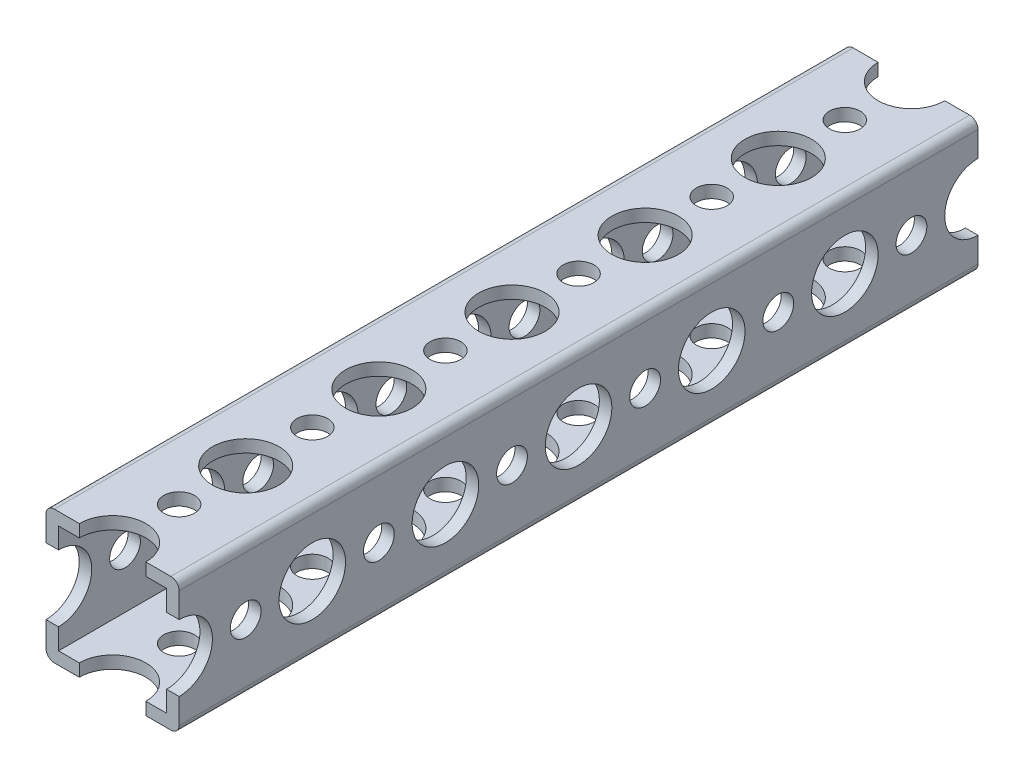
SolidWorks part; units mm, degrees
ref_plane "Front Plane" through (0, 0, 0) normal (0, 0, 1) x (1, 0, 0)
ref_plane "Top Plane" through (0, 0, 0) normal (0, 1, 0) x (1, 0, 0)
ref_plane "Right Plane" through (0, 0, 0) normal (1, 0, 0) x (0, 0, -1)
sketch "Sketch1" plane through (0, 0, 0) normal (0, 0, 1) x (1, 0, 0)
  line L1 (0, 0) -> (16, 0)
  line L2 (0, 0) -> (0, 16)
  line L3 (0, 16) -> (16, 16)
  line L4 (16, 0) -> (16, 16)
  dimension "D1" = 16
  dimension "D2" = 16
extrude "Extrude1" add sketch "Sketch1" against normal blind 96
sketch "Sketch2" plane through (0, 0, 0) normal (0, 0, 1) x (1, 0, 0)
  line L0 (-1.7793, 8) -> (18.8812, 8) construction
  line L1 (8, 16.9255) -> (8, -0.6999) construction
  line L3 (1.5, 14.5) -> (14.5, 14.5)
  line L4 (1.5, 14.5) -> (1.5, 1.5)
  line L5 (1.5, 1.5) -> (14.5, 1.5)
  line L6 (14.5, 14.5) -> (14.5, 1.5)
  line L7 (1.5, 14.5) -> (14.5, 1.5) construction
  line L8 (1.5, 1.5) -> (14.5, 14.5) construction
  point P4 (8, 8)
  dimension "D1" = 13
  dimension "D2" = 13
extrude "Extrude2" cut sketch "Sketch2" against normal through all
sketch "Sketch3" plane through (0, 16, 0) normal (0, 1, 0) x (1, 0, 0)
  line L0 (-10.6019, 48) -> (25.4979, 48) construction
  line L1 (8, -3.3001) -> (8, 305.034) construction
  line L2 (-10.6019, 80) -> (44.8988, 80) construction
  line L4 (16, 0) -> (0, 0) construction
  line L5 (-19.3069, 144) -> (85.0309, 144) construction
  circle A0 centre (8, 64) radius 4
  circle A1 centre (8, 32) radius 4
  circle A3 centre (8, 0) radius 4
  circle A4 centre (8, 96) radius 4
  circle A5 centre (8, 128) radius 4
  circle A6 centre (8, 160) radius 4
  circle A7 centre (8, 192) radius 4
  circle A8 centre (8, 224) radius 4
  circle A9 centre (8, 256) radius 4
  circle B0 centre (8, 48) radius 4
  circle B1 centre (8, 56) radius 1.85
  circle B2 centre (8, 40) radius 1.85
  circle B3 centre (8, 80) radius 4
  circle B4 centre (8, 88) radius 1.85
  circle B5 centre (8, 72) radius 1.85
  circle B6 centre (8, 16) radius 4
  circle B7 centre (8, 24) radius 1.85
  circle B8 centre (8, 8) radius 1.85
  circle B9 centre (8, 112) radius 4
  circle B10 centre (8, 120) radius 1.85
  circle B11 centre (8, 104) radius 1.85
  circle B12 centre (8, 144) radius 4
  circle B13 centre (8, 152) radius 1.85
  circle B14 centre (8, 136) radius 1.85
  circle B15 centre (8, 176) radius 4
  circle B16 centre (8, 184) radius 1.85
  circle B17 centre (8, 168) radius 1.85
  circle B18 centre (8, 208) radius 4
  circle B19 centre (8, 216) radius 1.85
  circle B20 centre (8, 200) radius 1.85
  circle B21 centre (8, 240) radius 4
  circle B22 centre (8, 248) radius 1.85
  circle B23 centre (8, 232) radius 1.85
  dimension "D1" = 24
  dimension "D2" = 16
  dimension "D4" = 16
  dimension "D5" = 32
  dimension "D7" = 16
  dimension "D13" = 48
  dimension "D3" = 24
  dimension "D6" = 64
  dimension "D8" = 48
  dimension "D9" = 32
  dimension "D10" = 64
  dimension "D11" = 96
  dimension "D14" = 16
  dimension "D15" = 80
  dimension "D16" = 112
sketch_block_instance "Block2-1"
sketch_block "Block2"
sketch_block_instance "Block2-4"
sketch_block_instance "Block2-6"
sketch_block_instance "Block2-11"
sketch_block_instance "Block2-12"
sketch_block_instance "Block2-17"
sketch_block_instance "Block2-18"
sketch_block_instance "Block2-19"
extrude "Extrude3" cut sketch "Sketch3" against normal through all
sketch "Sketch4" plane through (16, 0, 0) normal (1, 0, 0) x (0, 0, -1)
  line L0 (-4.9809, 8) -> (308.0277, 8) construction
  line L1 (48, 20.3919) -> (48, -4.2435) construction
  line L2 (0, 0) -> (0, 16) construction
  line L4 (80, -7.5844) -> (80, 23.8371) construction
  line L5 (144, 22.3836) -> (144, -28.3788) construction
  circle A0 centre (32, 8) radius 4
  circle A1 centre (64, 8) radius 4
  circle A2 centre (0, 8) radius 4
  circle A4 centre (96, 8) radius 4
  circle A5 centre (128, 8) radius 4
  circle A6 centre (160, 8) radius 4
  circle A7 centre (192, 8) radius 4
  circle A8 centre (224, 8) radius 4
  circle A9 centre (256, 8) radius 4
  circle B0 centre (48, 8.0742) radius 4
  circle B1 centre (40, 8.0742) radius 1.85
  circle B2 centre (56, 8.0742) radius 1.85
  circle B3 centre (80, 8) radius 4
  circle B4 centre (72, 8) radius 1.85
  circle B5 centre (88, 8) radius 1.85
  circle B6 centre (16, 8) radius 4
  circle B7 centre (8, 8) radius 1.85
  circle B8 centre (24, 8) radius 1.85
  circle B9 centre (112, 8) radius 4
  circle B10 centre (104, 8) radius 1.85
  circle B11 centre (120, 8) radius 1.85
  circle B12 centre (144, 8) radius 4
  circle B13 centre (136, 8) radius 1.85
  circle B14 centre (152, 8) radius 1.85
  circle B15 centre (176, 8) radius 4
  circle B16 centre (168, 8) radius 1.85
  circle B17 centre (184, 8) radius 1.85
  circle B18 centre (208, 8) radius 4
  circle B19 centre (200, 8) radius 1.85
  circle B20 centre (216, 8) radius 1.85
  circle B21 centre (240, 8) radius 4
  circle B22 centre (232, 8) radius 1.85
  circle B23 centre (248, 8) radius 1.85
  dimension "D3" = 16
  dimension "D5" = 32
  dimension "D7" = 16
  dimension "D13" = 16
  dimension "D1" = 24
  dimension "D2" = 24
  dimension "D4" = 16
  dimension "D6" = 64
  dimension "D8" = 48
  dimension "D9" = 32
  dimension "D10" = 64
  dimension "D11" = 96
  dimension "D14" = 48
  dimension "D15" = 80
  dimension "D16" = 112
sketch_block_instance "Block2-8"
sketch_block_instance "Block2-9"
sketch_block_instance "Block2-10"
sketch_block_instance "Block2-14"
sketch_block_instance "Block2-15"
sketch_block_instance "Block2-22"
sketch_block_instance "Block2-23"
sketch_block_instance "Block2-24"
extrude "Extrude4" cut sketch "Sketch4" against normal through all
fillet "Fillet1" radius 1 4 edges at (0, 0, -48) (16, 0, -48) (0, 16, -48) (16, 16, -48)
